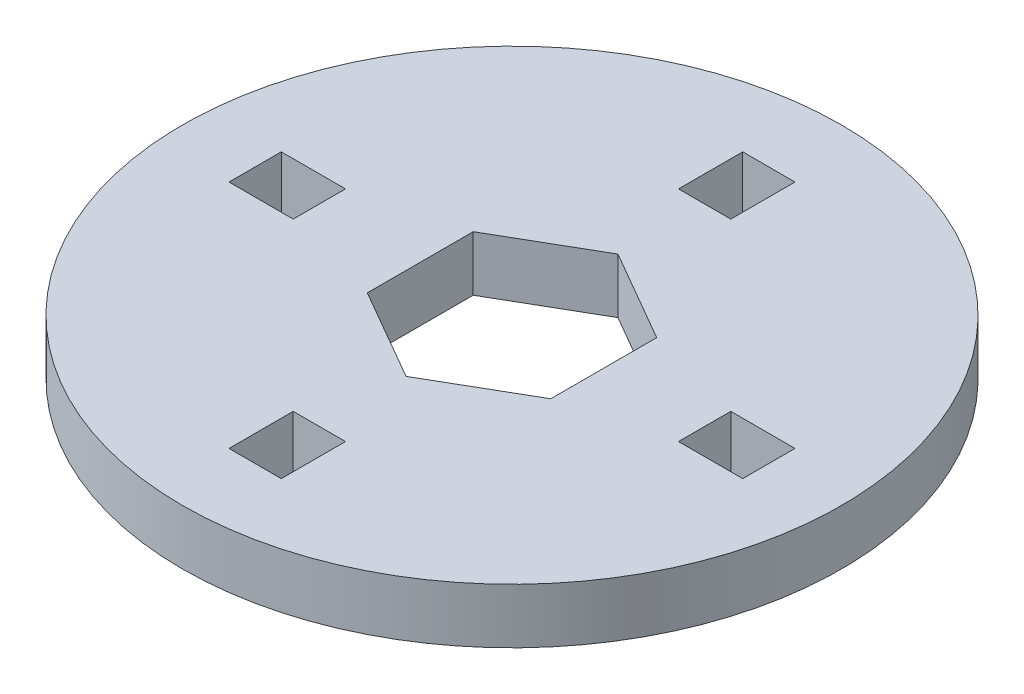
SolidWorks part; units mm, degrees
ref_plane "Front Plane" through (0, 0, 0) normal (0, 0, 1) x (1, 0, 0)
ref_plane "Top Plane" through (0, 0, 0) normal (0, 1, 0) x (1, 0, 0)
ref_plane "Right Plane" through (0, 0, 0) normal (1, 0, 0) x (0, 0, -1)
sketch "Sketch1" plane through (0, 0, 0) normal (0, 1, 0) x (1, 0, 0)
  line L4 (-10.5, -1.425) -> (-10.5, 1.425)
  line L5 (1.425, -10.5) -> (-1.425, -10.5)
  line L6 (1.425, -10.5) -> (1.425, -14)
  line L7 (1.425, -14) -> (-1.425, -14)
  line L8 (-1.425, -10.5) -> (-1.425, -14)
  line L9 (0, -14) -> (0, -10.5) construction
  line L10 (1.425, -12.25) -> (-1.425, -12.25) construction
  line L11 (-10.5, 1.425) -> (-14, 1.425)
  line L12 (-14, -1.425) -> (-14, 1.425)
  line L13 (-10.5, -1.425) -> (-14, -1.425)
  line L14 (-1.425, 10.5) -> (1.425, 10.5)
  line L15 (1.425, 10.5) -> (1.425, 14)
  line L16 (-1.425, 14) -> (1.425, 14)
  line L17 (-1.425, 10.5) -> (-1.425, 14)
  line L18 (10.5, 1.425) -> (10.5, -1.425)
  line L19 (10.5, -1.425) -> (14, -1.425)
  line L20 (14, 1.425) -> (14, -1.425)
  line L21 (10.5, 1.425) -> (14, 1.425)
  line L23 (0, -5.7735) -> (5, -2.8868)
  line L24 (5, -2.8868) -> (5, 2.8868)
  line L25 (5, 2.8868) -> (0, 5.7735)
  line L26 (0, 5.7735) -> (-5, 2.8868)
  line L27 (-5, 2.8868) -> (-5, -2.8868)
  line L28 (-5, -2.8868) -> (0, -5.7735)
  circle A0 centre (0, 0) radius 17.9627
  arc A1 (-17.9, -1.5) -> (-1.5, -17.9) centre (0, 0) ccw construction
  circle A2 centre (0, 0) radius 5 construction
  point P13 (0, -12.25)
  point P24 (0, 0)
  dimension "D2" = 10
  dimension "D1" = 4
extrude "Boss-Extrude1" add sketch "Sketch1" along normal blind 3
